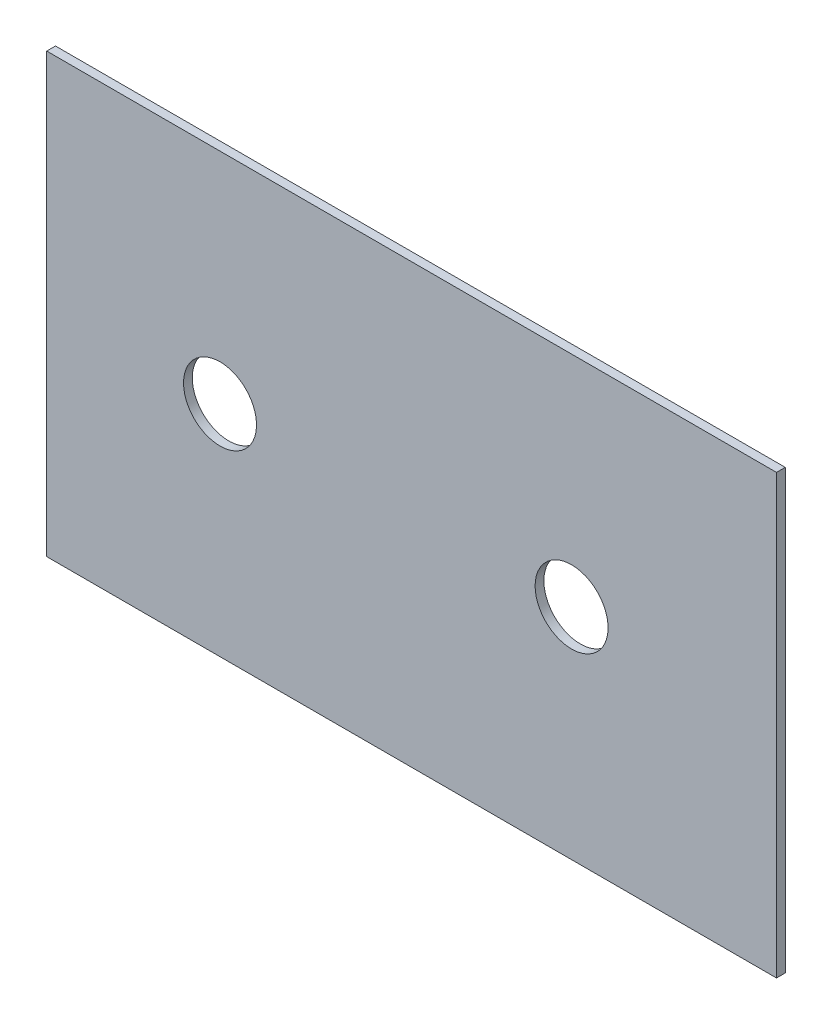
SolidWorks part; units mm, degrees
ref_plane "Front Plane" through (0, 0, 0) normal (0, 0, 1) x (1, 0, 0)
ref_plane "Top Plane" through (0, 0, 0) normal (0, 1, 0) x (1, 0, 0)
ref_plane "Right Plane" through (0, 0, 0) normal (1, 0, 0) x (0, 0, -1)
sketch "Sketch1" plane through (0, 0, 0) normal (0, 0, 1) x (1, 0, 0)
  line L1 (-63.5, -38.1) -> (63.5, -38.1)
  line L2 (-63.5, -38.1) -> (-63.5, 38.1)
  line L3 (-63.5, 38.1) -> (63.5, 38.1)
  line L4 (63.5, -38.1) -> (63.5, 38.1)
  line L5 (-63.5, -38.1) -> (63.5, 38.1) construction
  line L6 (-63.5, 38.1) -> (63.5, -38.1) construction
  point P0 (0, 0)
  dimension "D1" = 127
  dimension "D2" = 76.2
extrude "Boss-Extrude1" add sketch "Sketch1" along normal blind 1.524
sketch "Sketch2" plane through (0, 0, 0) normal (0, 0, -1) x (-1, 0, 0)
  circle A0 centre (-27.8406, 0) radius 6.35
  circle A1 centre (33.3442, 0) radius 6.35
  point P4 (-37.7271, 0)
  point P5 (-32.3491, 0)
  point P6 (-27.8406, 0)
  dimension "D1" = 12.7
  dimension "D2" = 12.7
extrude "Cut-Extrude1" cut sketch "Sketch2" against normal up to surface (1.524 mm away) up to face at (0, 0, 1.524)
